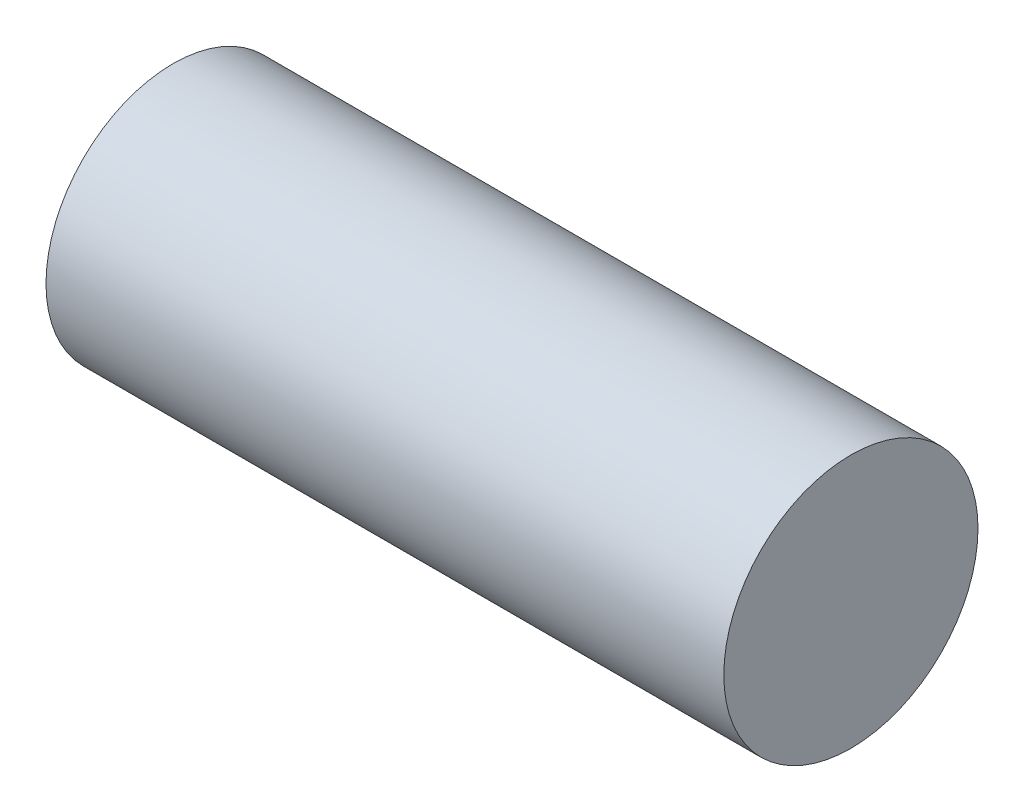
SolidWorks part; units mm, degrees
ref_plane "正面" through (0, 0, 0) normal (0, 0, 1) x (1, 0, 0)
ref_plane "平面" through (0, 0, 0) normal (0, 1, 0) x (1, 0, 0)
ref_plane "右側面" through (0, 0, 0) normal (1, 0, 0) x (0, 0, -1)
sketch "ｽｹｯﾁ2" plane through (0, 0, 0) normal (0, 0, 1) x (1, 0, 0)
  line L0 (0, 0) -> (0, -60)
  line L1 (0, -60) -> (320, -60)
  line L2 (160, -60) -> (160, -10)
  line L3 (160, -10) -> (150, -10)
  line L4 (150, -10) -> (110, -50)
  line L5 (110, -50) -> (10, -50)
  line L6 (10, -50) -> (10, 0)
  line L7 (10, 0) -> (0, 0)
  line L8 (310, -50) -> (310, 0)
  line L9 (210, -50) -> (310, -50)
  line L10 (170, -10) -> (210, -50)
  line L11 (160, -10) -> (170, -10)
  line L12 (320, 0) -> (320, -60)
  line L13 (310, 0) -> (320, 0)
  point P3 (155, -10)
  dimension "D1" = 160
  dimension "D2" = 100
  dimension "D3" = 60
  dimension "D4" = 50
  dimension "D5" = 10
  dimension "D6" = 45
  dimension "D7" = 10
revolve "回転1" add sketch "ｽｹｯﾁ2" angle 360 about L7
